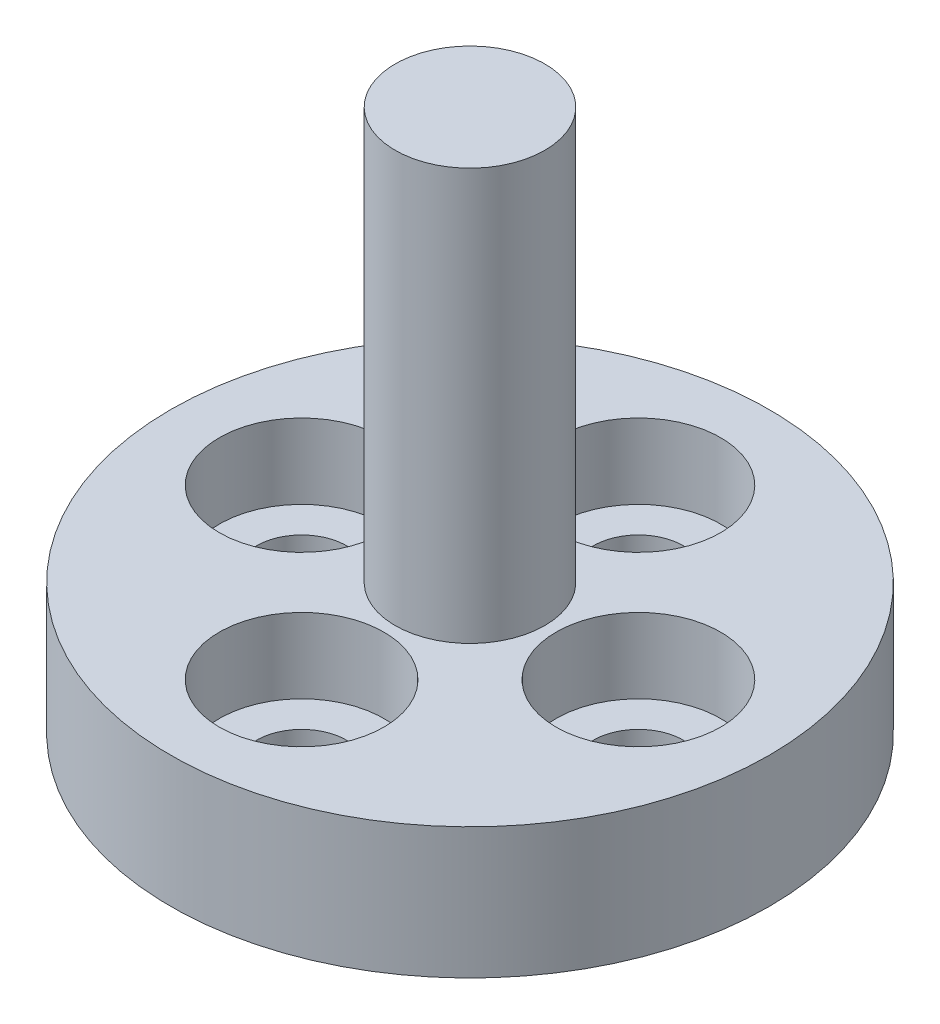
SolidWorks part; units mm, degrees
ref_plane "Front Plane" through (0, 0, 0) normal (0, 0, 1) x (1, 0, 0)
ref_plane "Top Plane" through (0, 0, 0) normal (0, 1, 0) x (1, 0, 0)
ref_plane "Right Plane" through (0, 0, 0) normal (1, 0, 0) x (0, 0, -1)
sketch "Sketch1" plane through (0, 0, 0) normal (0, 0, 1) x (1, 0, 0)
  line L1 (-4, -7.25) -> (4, -7.25)
  line L2 (-4, -7.25) -> (-4, 7.25)
  line L3 (-4, 7.25) -> (-2, 7.25)
  line L4 (4, -7.25) -> (4, -3.75)
  line L5 (-4, -7.25) -> (0, 0) construction
  line L6 (-4, 7.25) -> (4, -7.25) construction
  line L9 (4, -3.75) -> (-2, -3.75)
  line L10 (-2, 7.25) -> (-2, -3.75)
  point P0 (0, 0)
  dimension "D1" = 8
  dimension "D2" = 2
  dimension "D3" = 11
revolve "Revolve1" add sketch "Sketch1" angle 360 about L2
sketch "Sketch2" plane through (0, -3.75, 0) normal (0, 1, 0) x (1, 0, 0)
  line L0 (-8.5, 0) -> (0.5, 0) construction
  line L1 (-4, -4.5) -> (-4, 4.5) construction
  circle A0 centre (-4, 0) radius 4.5
  circle A1 centre (-4, 0) radius 8 construction
  point P8 (-4, 0)
  point P24 (-4, 0)
  dimension "D1" = 9
hole_wizard "CBORE for M2 SHCS2" positions "Sketch5" profile "Sketch6" counterbore size "M2" standard "ANSI Metric" end condition through all
sketch "Sketch5" plane through (0, -3.75, 0) normal (0, 1, 0) x (1, 0, 0)
  point P0 (-4, 4.5)
  point P3 (0.5, 0)
  point P6 (-4, -4.5)
  point P9 (-8.5, 0)
sketch "Sketch6" plane through (-4, -3.75, -4.5) normal (1, 0, 0) x (0, 0, 1)
  line L0 (0, 0) -> (0, 3.5)
  line L1 (0, 3.5) -> (1.2, 3.5)
  line L3 (1.2, 3.5) -> (1.2, 2)
  line L4 (1.2, 2) -> (2.2, 2)
  line L5 (2.2, 2) -> (2.2, 0)
  line L7 (2.2, 0) -> (0, 0)
  line L11 (0, -6.35) -> (0, 107.95) construction
  dimension "Thru Hole Dia." = 2.4
  dimension "Thru Hole Depth" = 3.5
  dimension "C'Bore Dia." = 4.4
  dimension "C'Bore Depth" = 2
